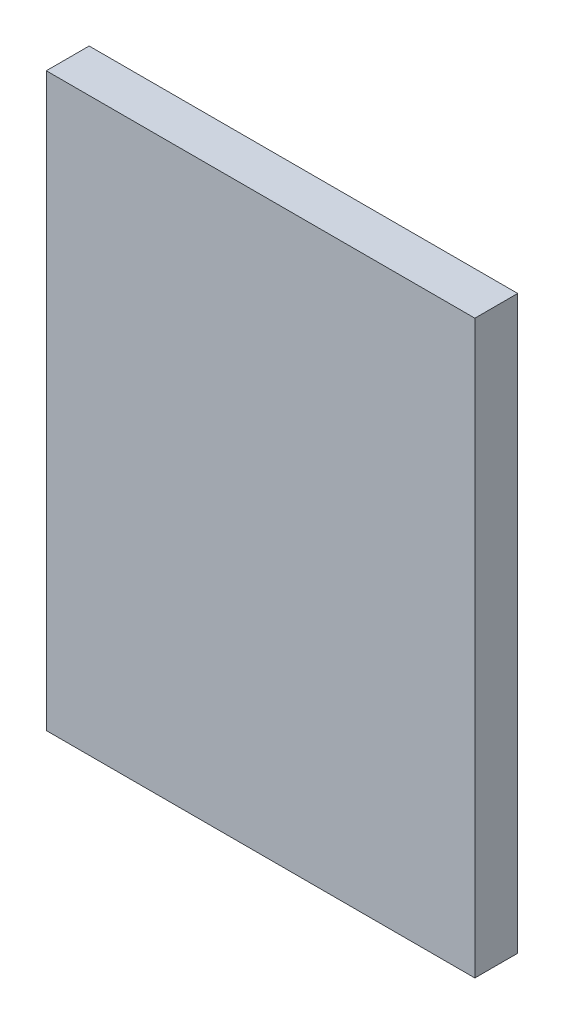
SolidWorks part; units mm, degrees
ref_plane "Piano frontale" through (0, 0, 0) normal (0, 0, 1) x (1, 0, 0)
ref_plane "Piano superiore" through (0, 0, 0) normal (0, 1, 0) x (1, 0, 0)
ref_plane "Piano destro" through (0, 0, 0) normal (1, 0, 0) x (0, 0, -1)
sketch "Schizzo1" plane through (0, 0, 0) normal (0, 0, 1) x (1, 0, 0)
  line L1 (0, 0) -> (300, 0)
  line L2 (0, 0) -> (0, -400)
  line L3 (0, -400) -> (300, -400)
  line L4 (300, 0) -> (300, -400)
  dimension "D1" = 400
  dimension "D2" = 300
extrude "Estrusione-Estrusione1" add sketch "Schizzo1" along normal blind 30
equation "\"D2@Schizzo1\"=\"D1@Estrusione-Estrusione1\"*10"
equation "\"D1@Schizzo1\"=sqr(160000)"
equation "\"D1@Estrusione-Estrusione1\"= 30"
